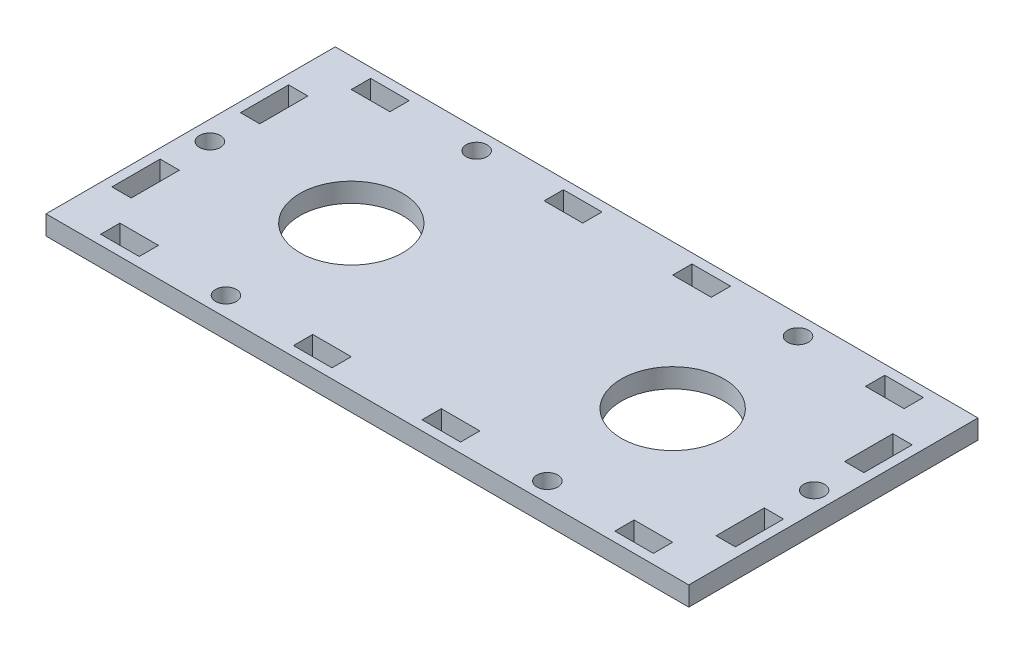
SolidWorks part; units mm, degrees
ref_plane "Front Plane" through (0, 0, 0) normal (0, 0, 1) x (1, 0, 0)
ref_plane "Top Plane" through (0, 0, 0) normal (0, 1, 0) x (1, 0, 0)
ref_plane "Right Plane" through (0, 0, 0) normal (1, 0, 0) x (0, 0, -1)
sketch "Sketch1" plane through (0, 0, 0) normal (0, 1, 0) x (1, 0, 0)
  line L1 (100, -45) -> (-100, -45)
  line L2 (100, -45) -> (100, 45)
  line L3 (100, 45) -> (-100, 45)
  line L4 (-100, -45) -> (-100, 45)
  line L5 (100, -45) -> (-100, 45) construction
  line L6 (100, 45) -> (-100, -45) construction
  point P0 (0, 0)
  dimension "D1" = 200
  dimension "D2" = 90
extrude "Boss-Extrude1" add sketch "Sketch1" along normal blind 6
sketch "Sketch2" plane through (0, 6, 0) normal (0, 1, 0) x (1, 0, 0)
  line L0 (0, 0) -> (0, 21.9987) construction
  line L1 (0, 0) -> (26.9936, 0) construction
  circle A0 centre (-50, 0) radius 16
  circle A1 centre (50, 0) radius 16
  dimension "D1" = 32
  dimension "D2" = 50
extrude "Cut-Extrude1" cut sketch "Sketch2" against normal up to next
sketch "Sketch3" plane through (0, 6, 0) normal (0, 1, 0) x (1, 0, 0)
  line L0 (0, 0) -> (0, 26.4622) construction
  line L1 (0, 0) -> (22.105, 0) construction
  line L2 (-100, 39) -> (100, 39) construction
  line L3 (-100, 45) -> (-100, -45) construction
  line L4 (100, -45) -> (100, 45) construction
  line L5 (100, 45) -> (-100, 45) construction
  line L6 (-50, 0) -> (-50, 45) construction
  line L7 (-74, 36) -> (-86, 36)
  line L8 (-74, 36) -> (-74, 42)
  line L9 (-74, 42) -> (-86, 42)
  line L10 (-86, 36) -> (-86, 42)
  line L11 (-74, 36) -> (-86, 42) construction
  line L12 (-74, 42) -> (-86, 36) construction
  line L13 (-26, 42) -> (-14, 36) construction
  line L14 (-26, 36) -> (-14, 42) construction
  line L15 (-14, 36) -> (-14, 42)
  line L16 (-26, 42) -> (-14, 42)
  line L17 (-26, 36) -> (-26, 42)
  line L18 (-26, 36) -> (-14, 36)
  line L19 (26, 36) -> (14, 42) construction
  line L20 (26, 42) -> (14, 36) construction
  line L21 (74, 42) -> (86, 36) construction
  line L22 (74, 36) -> (86, 42) construction
  line L23 (26, 36) -> (14, 36)
  line L24 (26, 36) -> (26, 42)
  line L25 (26, 42) -> (14, 42)
  line L26 (14, 36) -> (14, 42)
  line L27 (86, 36) -> (86, 42)
  line L28 (74, 42) -> (86, 42)
  line L29 (74, 36) -> (74, 42)
  line L30 (74, 36) -> (86, 36)
  line L31 (74, -36) -> (86, -42) construction
  line L32 (74, -42) -> (86, -36) construction
  line L33 (26, -42) -> (14, -36) construction
  line L34 (26, -36) -> (14, -42) construction
  line L35 (-26, -36) -> (-14, -42) construction
  line L36 (-26, -42) -> (-14, -36) construction
  line L37 (-74, -42) -> (-86, -36) construction
  line L38 (-74, -36) -> (-86, -42) construction
  line L39 (74, -36) -> (86, -36)
  line L40 (74, -36) -> (74, -42)
  line L41 (74, -42) -> (86, -42)
  line L42 (86, -36) -> (86, -42)
  line L43 (14, -36) -> (14, -42)
  line L44 (26, -42) -> (14, -42)
  line L45 (26, -36) -> (26, -42)
  line L46 (26, -36) -> (14, -36)
  line L47 (-26, -36) -> (-14, -36)
  line L48 (-26, -36) -> (-26, -42)
  line L49 (-26, -42) -> (-14, -42)
  line L50 (-14, -36) -> (-14, -42)
  line L51 (-86, -36) -> (-86, -42)
  line L52 (-74, -42) -> (-86, -42)
  line L53 (-74, -36) -> (-74, -42)
  line L54 (-74, -36) -> (-86, -36)
  line L55 (-94, 45) -> (-94, -45) construction
  line L56 (-100, -45) -> (100, -45) construction
  line L57 (-91, -27.5) -> (-97, -12.5) construction
  line L58 (-91, 12.5) -> (-97, 12.5)
  line L59 (-91, 12.5) -> (-91, 27.5)
  line L60 (-91, 27.5) -> (-97, 27.5)
  line L61 (-97, 12.5) -> (-97, 27.5)
  line L62 (-91, 12.5) -> (-97, 27.5) construction
  line L63 (-91, 27.5) -> (-97, 12.5) construction
  line L64 (-91, -12.5) -> (-97, -27.5) construction
  line L65 (-97, -12.5) -> (-97, -27.5)
  line L66 (-91, -27.5) -> (-97, -27.5)
  line L67 (-91, -12.5) -> (-91, -27.5)
  line L68 (-91, -12.5) -> (-97, -12.5)
  line L69 (91, -12.5) -> (97, -27.5) construction
  line L70 (91, 27.5) -> (97, 12.5) construction
  line L71 (91, 12.5) -> (97, 27.5) construction
  line L72 (91, -27.5) -> (97, -12.5) construction
  line L73 (91, -12.5) -> (97, -12.5)
  line L74 (91, -12.5) -> (91, -27.5)
  line L75 (91, -27.5) -> (97, -27.5)
  line L76 (97, -12.5) -> (97, -27.5)
  line L77 (97, 12.5) -> (97, 27.5)
  line L78 (91, 27.5) -> (97, 27.5)
  line L79 (91, 12.5) -> (91, 27.5)
  line L80 (91, 12.5) -> (97, 12.5)
  circle A0 centre (-50, 39) radius 3.25
  circle A1 centre (50, 39) radius 3.25
  circle A2 centre (50, -39) radius 3.25
  circle A3 centre (-50, -39) radius 3.25
  circle A4 centre (-94, 0) radius 3.25
  circle A5 centre (94, 0) radius 3.25
  point P13 (-80, 39)
  point P21 (-94, 20)
  point P26 (-20, 39)
  point P39 (20, 39)
  point P40 (80, 39)
  point P61 (80, -39)
  point P62 (20, -39)
  point P63 (-20, -39)
  point P64 (-80, -39)
  point P80 (-94, -20)
  point P91 (94, -20)
  point P92 (94, 20)
  dimension "D5" = 6.5
  dimension "D10" = 6.5
  dimension "D1" = 6
  dimension "D2" = 6
  dimension "D3" = 12
  dimension "D4" = 20
  dimension "D6" = 6
  dimension "D7" = 6
  dimension "D8" = 15
  dimension "D9" = 20
extrude "Cut-Extrude2" cut sketch "Sketch3" against normal up to next
